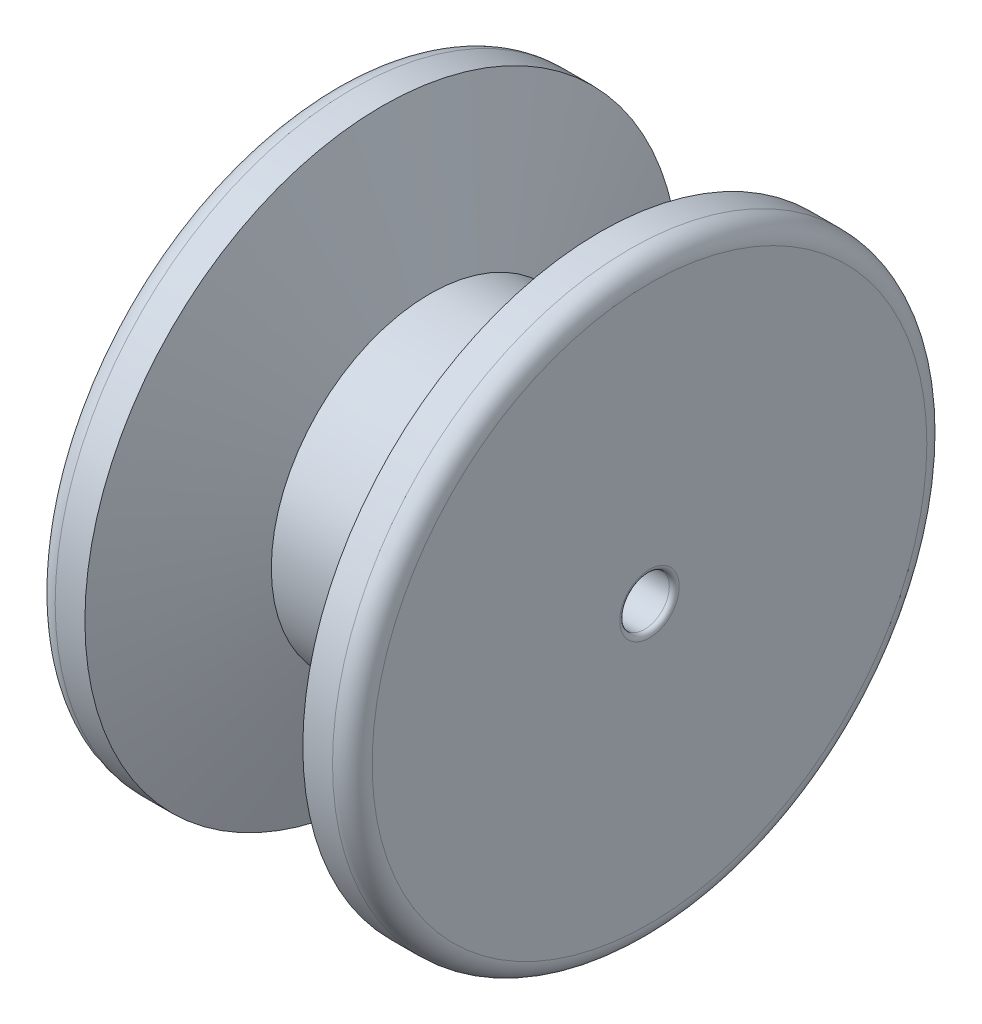
SolidWorks part; units mm, degrees
ref_plane "Alzado" through (0, 0, 0) normal (0, 0, 1) x (1, 0, 0)
ref_plane "Planta" through (0, 0, 0) normal (0, 1, 0) x (1, 0, 0)
ref_plane "Vista lateral" through (0, 0, 0) normal (1, 0, 0) x (0, 0, -1)
sketch "Croquis1" plane through (0, 0, 0) normal (0, 0, 1) x (1, 0, 0)
  line L0 (-29.0316, 0) -> (29.0316, 0) construction
  line L1 (-6.1794, 16) -> (6.1794, 16) construction
  line L2 (-16, 2.5) -> (16, 2.5) construction
  line L3 (-16, 2.5) -> (-16, 30)
  line L4 (-16, 30) -> (-11, 30)
  line L5 (-11, 30) -> (-6.1794, 16)
  line L6 (6.1794, 16) -> (11, 30) construction
  line L7 (11, 30) -> (16, 30) construction
  line L8 (16, 30) -> (16, 2.5) construction
  line L9 (0, 0) -> (0, 30) construction
  line L10 (-6.1794, 16) -> (0, 16)
  line L11 (0, 16) -> (0, 2.5)
  line L12 (0, 2.5) -> (-16, 2.5)
  point P0 (0, 16)
  point P4 (0, 0)
  point P6 (0, 2.5)
  point P8 (0, 0)
  point P18 (-13.5, 30)
  point P19 (13.5, 30)
  dimension "D1" = 14
  dimension "D2" = 22
  dimension "D3" = 5
  dimension "D4" = 2.5
  dimension "D5" = 60
  dimension "D6" = 38
revolve "Revolución1" add sketch "Croquis1" angle 360 about L0
fillet "Redondeo2" radius 2 1 edges at (-16, 0, 30)
fillet "Redondeo3" radius 0.5 1 edges at (-16, 0, 2.5)
sketch "Croquis2" plane through (0, 0, 0) normal (0, 0, 1) x (1, 0, 0)
  line L0 (-6.1794, 16) -> (-11, 30) construction
ref_plane "Plano1" through (-0.5991, -0.2063, 0) normal (0.9455, 0.3256, 0) x (-0.3256, 0.9455, 0)
ref_plane "Plano2" through (0, 5, 0) normal (0, 1, 0) x (1, 0, 0)
surface "Superficie-Equidistancia1" parameters "D1"=0.2
mirror "Simetría2" about plane through (0, 0, 0) normal (1, 0, 0) of bodies 101 167
